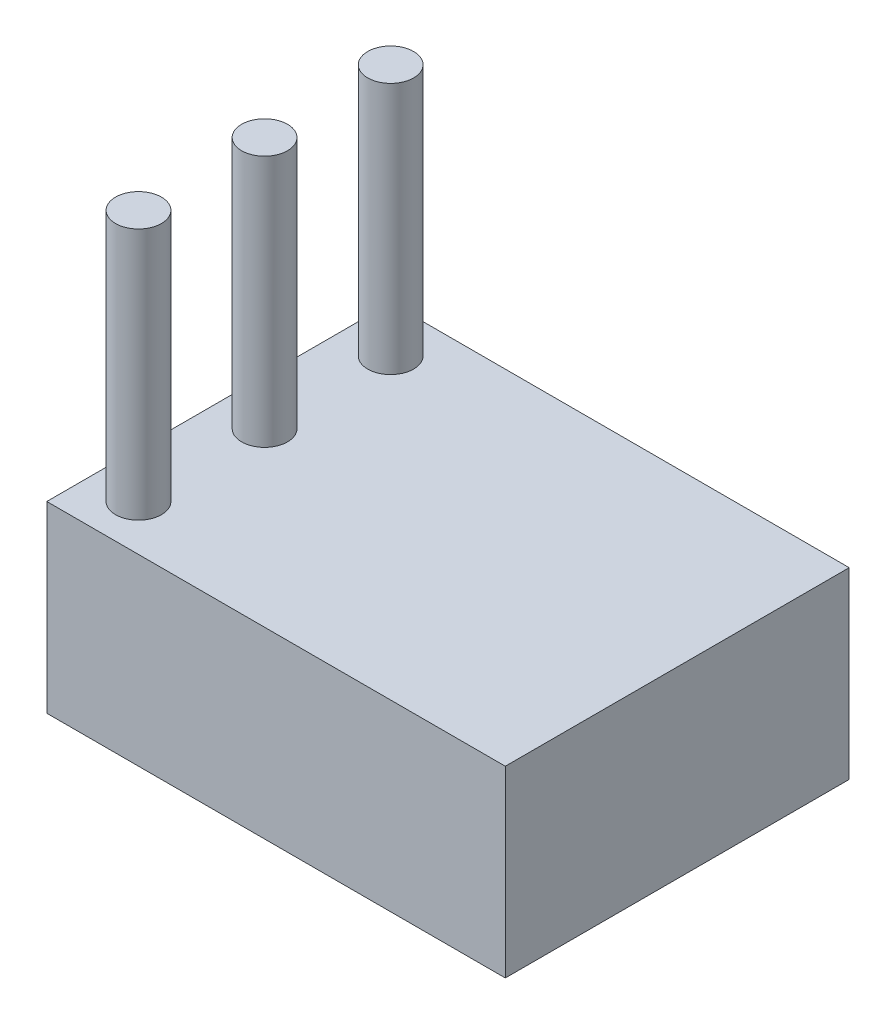
SolidWorks part; units mm, degrees
ref_plane "Front" through (0, 0, 0) normal (0, 0, 1) x (1, 0, 0)
ref_plane "Top" through (0, 0, 0) normal (0, 1, 0) x (1, 0, 0)
ref_plane "Right" through (0, 0, 0) normal (1, 0, 0) x (0, 0, -1)
sketch "Sketch1" plane through (0, 0, 0) normal (0, 1, 0) x (1, 0, 0)
  line L1 (-25.4, -19.05) -> (25.4, -19.05)
  line L2 (-25.4, -19.05) -> (-25.4, 19.05)
  line L3 (-25.4, 19.05) -> (25.4, 19.05)
  line L4 (25.4, -19.05) -> (25.4, 19.05)
  line L5 (-25.4, -19.05) -> (25.4, 19.05) construction
  line L6 (-25.4, 19.05) -> (25.4, -19.05) construction
  point P0 (0, 0)
  dimension "D1" = 50.8
  dimension "D2" = 38.1
extrude "Boss-Extrude1" add sketch "Sketch1" along normal blind 20.32
sketch "Sketch2" plane through (0, 20.32, 0) normal (0, 1, 0) x (1, 0, 0)
  line L0 (-20.32, 19.05) -> (-20.32, -19.05) construction
  line L1 (25.4, 19.05) -> (-25.4, 19.05) construction
  line L2 (-25.4, -19.05) -> (25.4, -19.05) construction
  line L3 (-25.4, 19.05) -> (-25.4, -19.05) construction
  line L4 (0, 0) -> (-35.5797, 0) construction
  circle A0 centre (-20.32, 13.97) radius 2.54
  circle A1 centre (-20.32, -13.97) radius 2.54
  circle A2 centre (-20.32, 0) radius 2.54
  dimension "D2" = 5.08
  dimension "D3" = 5.08
  dimension "D1" = 5.08
extrude "Boss-Extrude2" add sketch "Sketch2" along normal blind 27.94
